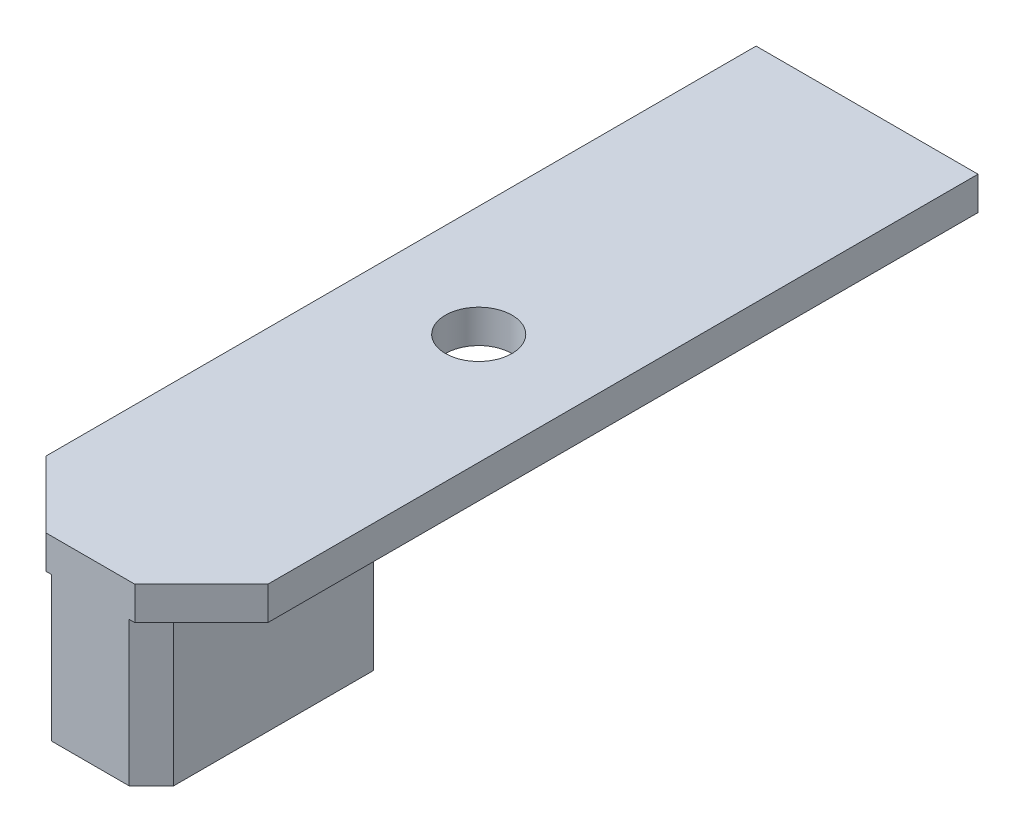
SolidWorks part; units mm, degrees
ref_plane "Front Plane" through (0, 0, 0) normal (0, 0, 1) x (1, 0, 0)
ref_plane "Top Plane" through (0, 0, 0) normal (0, 1, 0) x (1, 0, 0)
ref_plane "Right Plane" through (0, 0, 0) normal (1, 0, 0) x (0, 0, -1)
sketch "Sketch1" plane through (0, 0, 0) normal (0, 1, 0) x (1, 0, 0)
  line L0 (-7, 0) -> (-10, 3)
  line L1 (-3, 0) -> (-7, 0)
  line L2 (0, 3) -> (0, 35)
  line L3 (0, 35) -> (-10, 35)
  line L4 (-10, 3) -> (-10, 35)
  line L5 (0, 3) -> (-3, 0)
  point P0 (0, 0)
  point P3 (-10, 0)
  dimension "D1" = 10
  dimension "D2" = 35
extrude "Boss-Extrude1" add sketch "Sketch1" along normal blind 1.5
sketch "Sketch2" plane through (0, 0, 0) normal (0, -1, 0) x (1, 0, 0)
  line L0 (-7, 0) -> (-3, 0) construction
  line L1 (-3.25, 0) -> (-6.75, 0)
  line L2 (-2.25, -1) -> (-2.25, -10)
  line L3 (-2.25, -10) -> (-7.75, -10)
  line L4 (-7.75, -1) -> (-7.75, -10)
  line L5 (0, -35) -> (-10, -35) construction
  line L6 (-6.75, 0) -> (-7.75, -1)
  line L7 (-2.25, -1) -> (-3.25, 0)
  point P0 (-2.25, 0)
  point P3 (-7.75, 0)
  point P6 (-5, -35)
  dimension "D1" = 5.5
  dimension "D2" = 10
  dimension "D3" = 0
  dimension "D4" = 2.75
extrude "Boss-Extrude2" add sketch "Sketch2" along normal blind 6.5
sketch "Sketch3" plane through (0, 1.5, 0) normal (0, 1, 0) x (1, 0, 0)
  line L0 (0, 35) -> (-10, 35) construction
  line L1 (0, 3) -> (0, 35) construction
  circle A0 centre (-5, 17.5) radius 1.5
  dimension "D1" = 17.5
  dimension "D2" = 3
  dimension "D3" = 5
extrude "Cut-Extrude1" cut sketch "Sketch3" against normal blind 6.5
